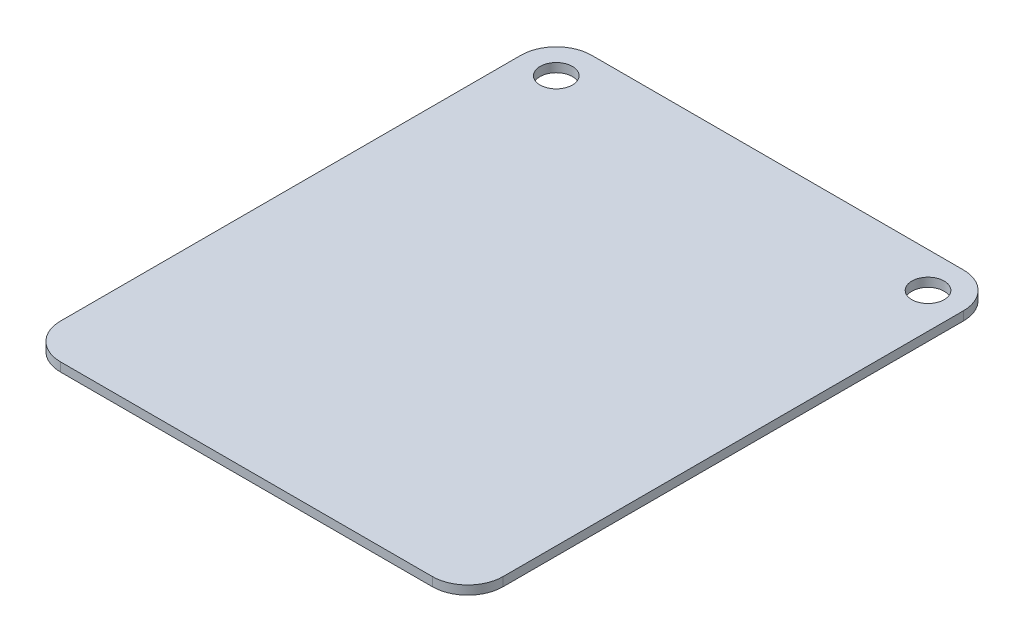
SolidWorks part; units mm, degrees
ref_plane "Front" through (0, 0, 0) normal (0, 0, 1) x (1, 0, 0)
ref_plane "Top" through (0, 0, 0) normal (0, 1, 0) x (1, 0, 0)
ref_plane "Right" through (0, 0, 0) normal (1, 0, 0) x (0, 0, -1)
sketch "Sketch1" plane through (0, 0, 0) normal (0, 1, 0) x (1, 0, 0)
  line L0 (0, 30) -> (0, 0) construction
  line L1 (-21, 30) -> (21, 30)
  line L2 (-25, 26) -> (-25, -26)
  line L3 (-21, -30) -> (21, -30)
  line L4 (25, 26) -> (25, -26)
  line L5 (0, 0) -> (25, 0) construction
  circle A0 centre (-21, 26) radius 1.825
  circle A1 centre (21, 26) radius 1.825
  arc A4 (-25, -26) -> (-21, -30) centre (-21, -26) ccw
  arc A5 (21, -30) -> (25, -26) centre (21, -26) ccw
  arc A6 (21, 30) -> (25, 26) centre (21, 26) cw
  arc A7 (-21, 30) -> (-25, 26) centre (-21, 26) ccw
  dimension "D4" = 3.65
  dimension "D1" = 50
  dimension "D2" = 60
  dimension "D3" = 42
extrude "Boss-Extrude1" add sketch "Sketch1" along normal blind 1
